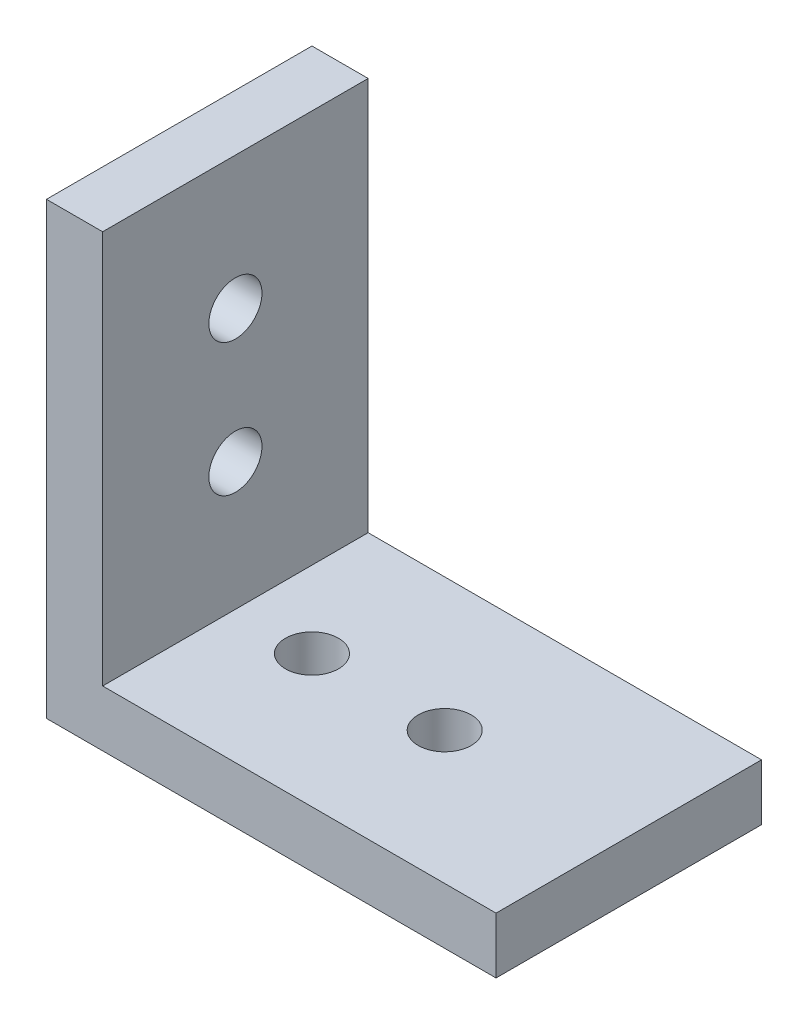
SolidWorks part; units mm, degrees
ref_plane "Front Plane" through (0, 0, 0) normal (0, 0, 1) x (1, 0, 0)
ref_plane "Top Plane" through (0, 0, 0) normal (0, 1, 0) x (1, 0, 0)
ref_plane "Right Plane" through (0, 0, 0) normal (1, 0, 0) x (0, 0, -1)
sketch "Sketch1" plane through (0, 0, 0) normal (1, 0, 0) x (0, 0, -1)
  line L1 (0, 0) -> (15, 0)
  line L2 (0, 0) -> (0, 25.4)
  line L3 (0, 25.4) -> (15, 25.4)
  line L4 (15, 0) -> (15, 25.4)
  dimension "D1" = 25.4
  dimension "D2" = 15
extrude "Boss-Extrude1" add sketch "Sketch1" along normal blind 3.175
sketch "Sketch2" plane through (3.175, 0, 0) normal (1, 0, 0) x (0, 0, -1)
  line L0 (15, 0) -> (15, 25.4) construction
  line L1 (0, 0) -> (15, 0)
  line L2 (0, 0) -> (0, 3.175)
  line L3 (0, 3.175) -> (15, 3.175)
  line L4 (15, 0) -> (15, 3.175)
  dimension "D1" = 3.175
extrude "Boss-Extrude2" add sketch "Sketch2" along normal blind 22.225
sketch "Sketch3" plane through (0, 0, 0) normal (0, -1, 0) x (1, 0, 0)
  line L0 (0, -7.5) -> (7.5, -7.5)
  line L1 (0, 0) -> (0, -15) construction
  line L2 (7.5, -7.5) -> (15, -7.5)
  circle A0 centre (7.5, -7.5) radius 1.5
  circle A1 centre (15, -7.5) radius 1.5
  dimension "D1" = 7.5
  dimension "D2" = 7.5
extrude "Cut-Extrude2" cut sketch "Sketch3" against normal through all contours A0 | A1
sketch "Sketch4" plane through (3.175, 0, 0) normal (1, 0, 0) x (0, 0, -1)
  line L0 (7.5, 25.4) -> (7.5, 10.4)
  line L1 (15, 25.4) -> (0, 25.4) construction
  circle A0 centre (7.5, 17.9) radius 1.5
  circle A1 centre (7.5, 10.4) radius 1.5
  dimension "D1" = 15
extrude "Cut-Extrude3" cut sketch "Sketch4" against normal through all contours A0 | A1
